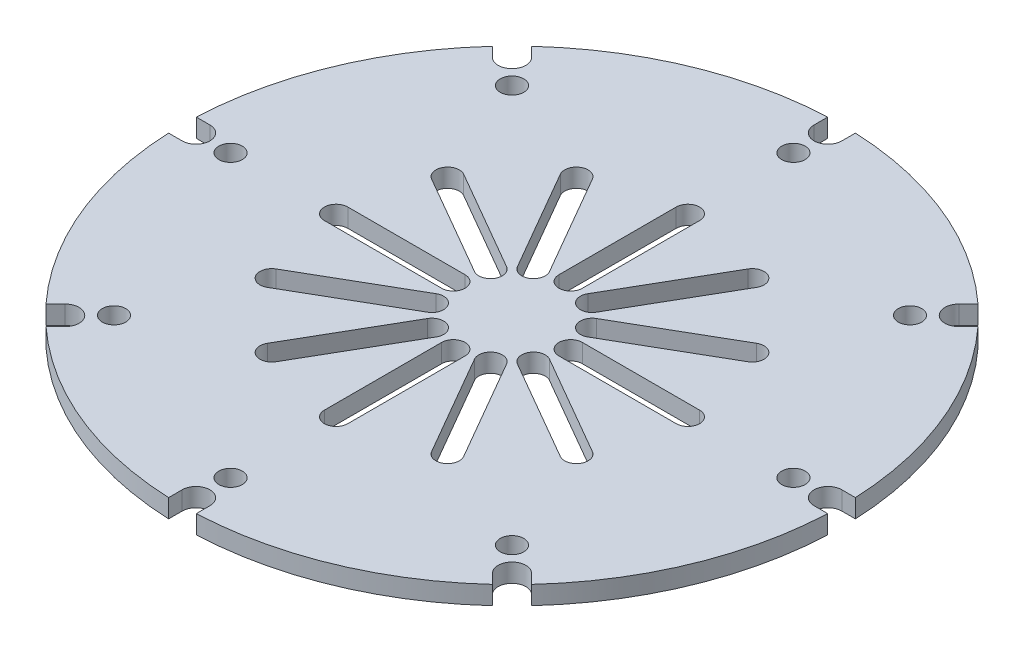
SolidWorks part; units mm, degrees
ref_plane "Front Plane" through (0, 0, 0) normal (0, 0, 1) x (1, 0, 0)
ref_plane "Top Plane" through (0, 0, 0) normal (0, 1, 0) x (1, 0, 0)
ref_plane "Right Plane" through (0, 0, 0) normal (1, 0, 0) x (0, 0, -1)
sketch "Sketch1" plane through (0, 0, 0) normal (0, 1, 0) x (1, 0, 0)
  line L0 (0, 0) -> (0, 12.192) construction
  circle A0 centre (0, 0) radius 14.2875
  circle A2 centre (0, 12.192) radius 0.508
  circle A3 centre (8.621, 8.621) radius 0.508
  circle A4 centre (12.192, 0) radius 0.508
  circle A5 centre (8.621, -8.621) radius 0.508
  circle A6 centre (0, -12.192) radius 0.508
  circle A7 centre (-8.621, -8.621) radius 0.508
  circle A8 centre (-12.192, 0) radius 0.508
  circle A9 centre (-8.621, 8.621) radius 0.508
  point P22 (0, 0)
  dimension "D1" = 12.192
  dimension "D2" = 28.575
  dimension "D3" = 8
extrude "Boss-Extrude1" add sketch "Sketch1" along normal blind 0.8
sketch "Sketch2" plane through (0, 0.8, 0) normal (0, 1, 0) x (1, 0, 0)
  line L0 (-0.6, 14.2749) -> (-0.6, -0.2634)
  line L1 (0, 0) -> (0, 13.0875) construction
  line L2 (0.6, 14.2749) -> (0.6, -0.2634)
  line L3 (10.5181, 9.6696) -> (0.238, -0.6105)
  line L4 (9.6696, 10.5181) -> (-0.6105, 0.238)
  line L5 (14.2749, -0.6) -> (-0.2634, -0.6)
  line L6 (14.2749, 0.6) -> (-0.2634, 0.6)
  line L7 (9.6696, -10.5181) -> (-0.6105, -0.238)
  line L8 (10.5181, -9.6696) -> (0.238, 0.6105)
  line L9 (-0.6, -14.2749) -> (-0.6, 0.2634)
  line L10 (0.6, -14.2749) -> (0.6, 0.2634)
  line L11 (-10.5181, -9.6696) -> (-0.238, 0.6105)
  line L12 (-9.6696, -10.5181) -> (0.6105, -0.238)
  line L13 (-14.2749, 0.6) -> (0.2634, 0.6)
  line L14 (-14.2749, -0.6) -> (0.2634, -0.6)
  line L15 (-9.6696, 10.5181) -> (0.6105, 0.238)
  line L16 (-10.5181, 9.6696) -> (-0.238, -0.6105)
  circle A0 centre (0, 0) radius 14.2875 construction
  arc A1 (-0.6, 13.6875) -> (0.6, 13.6875) centre (0, 13.6875) ccw
  circle A2 centre (0, 0) radius 14.2875
  arc A3 (9.2543, 10.1028) -> (10.1028, 9.2543) centre (9.6785, 9.6785) ccw
  arc A4 (13.6875, 0.6) -> (13.6875, -0.6) centre (13.6875, 0) ccw
  arc A5 (10.1028, -9.2543) -> (9.2543, -10.1028) centre (9.6785, -9.6785) ccw
  arc A6 (0.6, -13.6875) -> (-0.6, -13.6875) centre (0, -13.6875) ccw
  arc A7 (-9.2543, -10.1028) -> (-10.1028, -9.2543) centre (-9.6785, -9.6785) ccw
  arc A8 (-13.6875, -0.6) -> (-13.6875, 0.6) centre (-13.6875, 0) ccw
  arc A9 (-10.1028, 9.2543) -> (-9.2543, 10.1028) centre (-9.6785, 9.6785) ccw
  point P64 (0, 0)
  circle M10 centre (0, 0) radius 14.2875
  dimension "D2" = 1.2
  dimension "D4" = 8
  dimension "D3" = 13.0875
  dimension "D1" = 1.2
extrude "Cut-Extrude1" cut sketch "Sketch2" against normal blind 0.8 contours L4 A3 L3 M10 | L6 A4 L5 M10 | L0 A1 L2 M10 | L8 A5 L7 M10 | L10 A6 L9 M10 | L12 A7 L11 M10 | L14 A8 L13 M10 | L16 A9 L15 M10
sketch "Sketch3" plane through (0, 0.8, 0) normal (0, 1, 0) x (1, 0, 0)
  line L0 (0, 2.54) -> (0, 7.62) construction
  line L1 (-0.508, 2.54) -> (-0.508, 7.62)
  line L2 (0.508, 2.54) -> (0.508, 7.62)
  line L3 (1.27, 2.1997) -> (3.81, 6.5991) construction
  line L4 (0.8301, 2.4537) -> (3.3701, 6.8531)
  line L5 (1.7099, 1.9457) -> (4.2499, 6.3451)
  line L6 (2.1997, 1.27) -> (6.5991, 3.81) construction
  line L7 (1.9457, 1.7099) -> (6.3451, 4.2499)
  line L8 (2.4537, 0.8301) -> (6.8531, 3.3701)
  line L9 (2.54, 0) -> (7.62, 0) construction
  line L10 (2.54, 0.508) -> (7.62, 0.508)
  line L11 (2.54, -0.508) -> (7.62, -0.508)
  line L12 (2.1997, -1.27) -> (6.5991, -3.81) construction
  line L13 (2.4537, -0.8301) -> (6.8531, -3.3701)
  line L14 (1.9457, -1.7099) -> (6.3451, -4.2499)
  line L15 (1.27, -2.1997) -> (3.81, -6.5991) construction
  line L16 (1.7099, -1.9457) -> (4.2499, -6.3451)
  line L17 (0.8301, -2.4537) -> (3.3701, -6.8531)
  line L18 (0, -2.54) -> (0, -7.62) construction
  line L19 (0.508, -2.54) -> (0.508, -7.62)
  line L20 (-0.508, -2.54) -> (-0.508, -7.62)
  line L21 (-1.27, -2.1997) -> (-3.81, -6.5991) construction
  line L22 (-0.8301, -2.4537) -> (-3.3701, -6.8531)
  line L23 (-1.7099, -1.9457) -> (-4.2499, -6.3451)
  line L24 (-2.1997, -1.27) -> (-6.5991, -3.81) construction
  line L25 (-1.9457, -1.7099) -> (-6.3451, -4.2499)
  line L26 (-2.4537, -0.8301) -> (-6.8531, -3.3701)
  line L27 (-2.54, 0) -> (-7.62, 0) construction
  line L28 (-2.54, -0.508) -> (-7.62, -0.508)
  line L29 (-2.54, 0.508) -> (-7.62, 0.508)
  line L30 (-2.1997, 1.27) -> (-6.5991, 3.81) construction
  line L31 (-2.4537, 0.8301) -> (-6.8531, 3.3701)
  line L32 (-1.9457, 1.7099) -> (-6.3451, 4.2499)
  line L33 (-1.27, 2.1997) -> (-3.81, 6.5991) construction
  line L34 (-1.7099, 1.9457) -> (-4.2499, 6.3451)
  line L35 (-0.8301, 2.4537) -> (-3.3701, 6.8531)
  arc A0 (-0.508, 2.54) -> (0.508, 2.54) centre (0, 2.54) ccw
  arc A1 (0.508, 7.62) -> (-0.508, 7.62) centre (0, 7.62) ccw
  arc A2 (0.8301, 2.4537) -> (1.7099, 1.9457) centre (1.27, 2.1997) ccw
  arc A3 (4.2499, 6.3451) -> (3.3701, 6.8531) centre (3.81, 6.5991) ccw
  arc A4 (1.9457, 1.7099) -> (2.4537, 0.8301) centre (2.1997, 1.27) ccw
  arc A5 (6.8531, 3.3701) -> (6.3451, 4.2499) centre (6.5991, 3.81) ccw
  arc A6 (2.54, 0.508) -> (2.54, -0.508) centre (2.54, 0) ccw
  arc A7 (7.62, -0.508) -> (7.62, 0.508) centre (7.62, 0) ccw
  arc A8 (2.4537, -0.8301) -> (1.9457, -1.7099) centre (2.1997, -1.27) ccw
  arc A9 (6.3451, -4.2499) -> (6.8531, -3.3701) centre (6.5991, -3.81) ccw
  arc A10 (1.7099, -1.9457) -> (0.8301, -2.4537) centre (1.27, -2.1997) ccw
  arc A11 (3.3701, -6.8531) -> (4.2499, -6.3451) centre (3.81, -6.5991) ccw
  arc A12 (0.508, -2.54) -> (-0.508, -2.54) centre (0, -2.54) ccw
  arc A13 (-0.508, -7.62) -> (0.508, -7.62) centre (0, -7.62) ccw
  arc A14 (-0.8301, -2.4537) -> (-1.7099, -1.9457) centre (-1.27, -2.1997) ccw
  arc A15 (-4.2499, -6.3451) -> (-3.3701, -6.8531) centre (-3.81, -6.5991) ccw
  arc A16 (-1.9457, -1.7099) -> (-2.4537, -0.8301) centre (-2.1997, -1.27) ccw
  arc A17 (-6.8531, -3.3701) -> (-6.3451, -4.2499) centre (-6.5991, -3.81) ccw
  arc A18 (-2.54, -0.508) -> (-2.54, 0.508) centre (-2.54, 0) ccw
  arc A19 (-7.62, 0.508) -> (-7.62, -0.508) centre (-7.62, 0) ccw
  arc A20 (-2.4537, 0.8301) -> (-1.9457, 1.7099) centre (-2.1997, 1.27) ccw
  arc A21 (-6.3451, 4.2499) -> (-6.8531, 3.3701) centre (-6.5991, 3.81) ccw
  arc A22 (-1.7099, 1.9457) -> (-0.8301, 2.4537) centre (-1.27, 2.1997) ccw
  arc A23 (-3.3701, 6.8531) -> (-4.2499, 6.3451) centre (-3.81, 6.5991) ccw
  point P3 (0, 5.08)
  point P9 (0, 0)
  point P14 (2.54, 4.3994)
  point P21 (4.3994, 2.54)
  point P28 (5.08, 0)
  point P35 (4.3994, -2.54)
  point P42 (2.54, -4.3994)
  point P49 (0, -5.08)
  point P56 (-2.54, -4.3994)
  point P63 (-4.3994, -2.54)
  point P70 (-5.08, 0)
  point P77 (-4.3994, 2.54)
  point P84 (-2.54, 4.3994)
  point P89 (0, 0)
  dimension "D1" = 1.016
  dimension "D2" = 5.08
  dimension "D3" = 2.54
  dimension "D4" = 12
extrude "Cut-Extrude2" cut sketch "Sketch3" against normal through all
